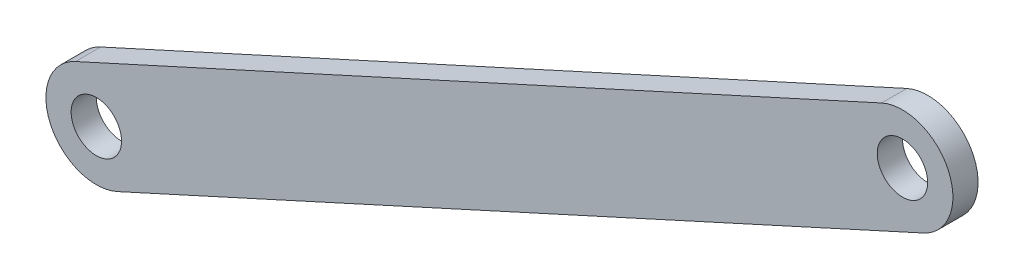
SolidWorks part; units mm, degrees
ref_plane "Front" through (0, 0, 0) normal (0, 0, 1) x (1, 0, 0)
ref_plane "Top" through (0, 0, 0) normal (0, 1, 0) x (1, 0, 0)
ref_plane "Right" through (0, 0, 0) normal (1, 0, 0) x (0, 0, -1)
sketch "Sketch1" plane through (0, 0, 0) normal (0, 0, 1) x (1, 0, 0)
  line L0 (-74.7944, 8.1432) -> (-24.0135, 31.2721) construction
  line L1 (-76.1104, 11.0326) -> (-25.3296, 34.1615)
  line L2 (-73.4783, 5.2538) -> (-22.6975, 28.3827)
  arc A0 (-76.1104, 11.0326) -> (-73.4783, 5.2538) centre (-74.7944, 8.1432) ccw
  arc A1 (-22.6975, 28.3827) -> (-25.3296, 34.1615) centre (-24.0135, 31.2721) ccw
  circle A2 centre (-24.0135, 31.2721) radius 1.5875
  circle A3 centre (-74.7944, 8.1432) radius 1.5875
  point P4 (-49.404, 19.7076)
  dimension "D1" = 3.175
  dimension "D2" = 6.35
extrude "Boss-Extrude1" add sketch "Sketch1" along normal blind 1.5875 from offset 1.5875
